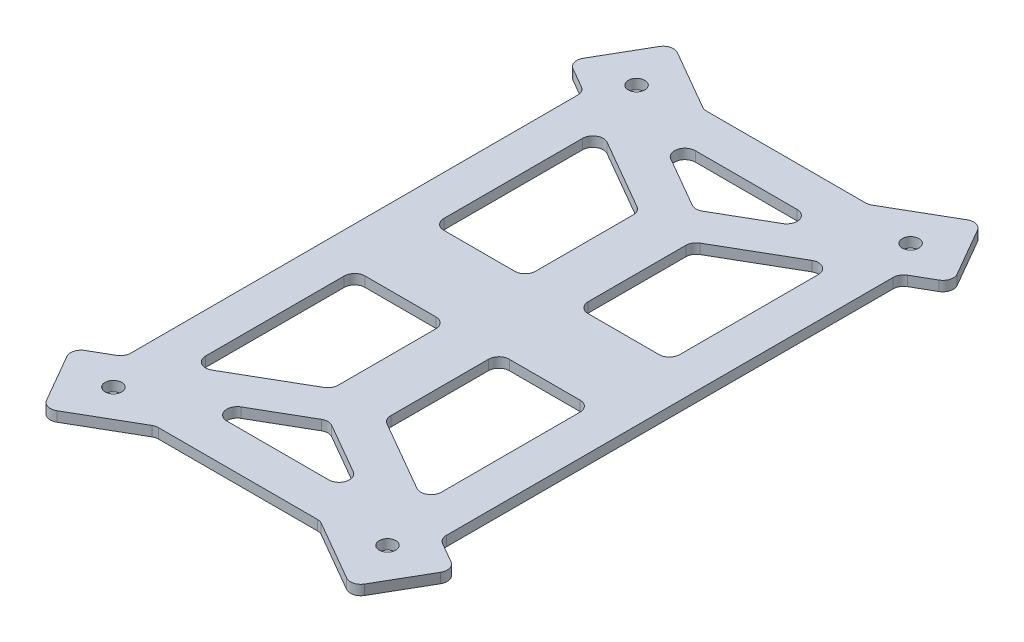
SolidWorks part; units mm, degrees
material "PA Type 6"
ref_plane "Front Plane" through (0, 0, 0) normal (0, 0, 1) x (1, 0, 0)
ref_plane "Top Plane" through (0, 0, 0) normal (0, 1, 0) x (1, 0, 0)
ref_plane "Right Plane" through (0, 0, 0) normal (1, 0, 0) x (0, 0, -1)
sketch "UPR FRAME PLATE ORIG SKETCH" plane through (0, 0, 0) normal (0, 1, 0) x (1, 0, 0)
  line L0 (-16.51, -144.7038) -> (-11.43, -142.1638)
  line L1 (-20.2311, 0) -> (20.2311, 0)
  line L2 (-24.0411, -3.81) -> (-24.0411, -144.7038)
  line L3 (-24.0411, -144.7038) -> (24.0411, -144.7038)
  line L4 (24.0411, -3.81) -> (24.0411, -144.7038)
  line L5 (-11.43, -142.1638) -> (11.43, -142.1638)
  line L6 (11.43, -142.1638) -> (16.51, -144.7038)
  line L7 (0, -144.7038) -> (0, 0) construction
  line L8 (-20.955, -60.6425) -> (20.955, -60.6425) construction
  line L9 (-18.034, -5.08) -> (18.034, -5.08) construction
  line L10 (-20.955, -140.6398) -> (20.955, -140.6398) construction
  circle A0 centre (20.955, -60.6425) radius 4.064
  circle A1 centre (-20.955, -60.6425) radius 4.064
  circle A2 centre (-20.955, -60.6425) radius 1.27
  circle A3 centre (20.955, -60.6425) radius 1.27
  circle A4 centre (-18.034, -5.08) radius 1.27
  circle A5 centre (18.034, -5.08) radius 1.27
  circle A6 centre (-20.955, -140.6398) radius 4.064
  circle A7 centre (20.955, -140.6398) radius 4.064
  circle A8 centre (-20.955, -140.6398) radius 1.27
  circle A9 centre (20.955, -140.6398) radius 1.27
  arc A10 (24.0411, -3.81) -> (20.2311, 0) centre (20.2311, -3.81) ccw
  arc A11 (-20.2311, 0) -> (-24.0411, -3.81) centre (-20.2311, -3.81) ccw
  point P4 (0, 0)
  point P15 (0, -60.6425)
  point P23 (0, -5.08)
  point P28 (0, -140.6398)
  point P35 (-24.0411, 0)
  dimension "D6" = 50.038
  dimension "D7" = 41.91
  dimension "D10" = 2.54
  dimension "D12" = 3.81
  dimension "D13" = 8.128
  dimension "D1" = 144.7038
  dimension "D2" = 48.0822
  dimension "D3" = 2.54
  dimension "D4" = 22.86
  dimension "D5" = 33.02
  dimension "D8" = 36.068
  dimension "D9" = 5.08
  dimension "D11" = 60.6425
sketch "Sketch2" plane through (0, 0, 0) normal (0, 1, 0) x (1, 0, 0)
  line L0 (0, -144.7038) -> (0, 0) construction
  line L1 (-24.13, -58.7311) -> (24.13, -58.7311)
  line L2 (-24.13, -58.7311) -> (-24.13, -142.5511)
  line L3 (-24.13, -142.5511) -> (24.13, -142.5511)
  line L4 (24.13, -58.7311) -> (24.13, -142.5511)
  line L5 (-20.955, -60.6425) -> (-20.955, -140.6398) construction
  line L6 (-20.955, -100.6411) -> (-46.355, -100.6411) construction
  circle A0 centre (-20.955, -60.6425) radius 1.27 construction
  circle A1 centre (20.955, -60.6425) radius 1.27 construction
  circle A2 centre (-20.955, -140.6398) radius 1.27 construction
  circle A3 centre (20.955, -140.6398) radius 1.27 construction
  circle A4 centre (-20.955, -60.6425) radius 1.27
  circle A5 centre (20.955, -60.6425) radius 1.27
  circle A6 centre (-20.955, -140.6398) radius 1.27
  circle A7 centre (20.955, -140.6398) radius 1.27
  point P16 (0, -58.7311)
  point P21 (-24.13, -100.6411)
  dimension "D1" = 83.82
  dimension "D2" = 48.26
extrude "Boss-Extrude1" add sketch "Sketch2" along normal blind 1.524 contours L4 L1 L2 L3 A7 A6 A5 A4
sketch "Sketch3" plane through (0, 0, 0) normal (0, 1, 0) x (1, 0, 0)
  line L0 (20.955, -60.6425) -> (26.4543, -57.4675) construction
  line L1 (-2.921, -67.6816) -> (23.5333, -52.4082)
  line L2 (-2.921, -67.6816) -> (2.921, -77.8002)
  line L3 (23.5333, -52.4082) -> (29.3753, -62.5268)
  line L4 (2.921, -77.8002) -> (29.3753, -62.5268)
  line L5 (-2.921, -67.6816) -> (29.3753, -62.5268) construction
  line L6 (23.5333, -52.4082) -> (2.921, -77.8002) construction
  line L8 (-24.13, -58.7311) -> (24.13, -58.7311) construction
  line L9 (0, -58.7312) -> (0, 0) construction
  circle A0 centre (20.955, -60.6425) radius 1.27 construction
  circle A1 centre (20.955, -60.6425) radius 1.27
  point P3 (26.4543, -57.4675)
  point P4 (13.2271, -65.1042)
  point P14 (0, -72.7409)
  dimension "D1" = 11.684
  dimension "D2" = 30
  dimension "D3" = 6.35
extrude "Boss-Extrude2" add sketch "Sketch3" along normal through all
ref_plane "CNTR OF LENGTH PLANE" through (0, 0, 100.6411) normal (0, 0, 1) x (1, 0, 0)
mirror "Mirror1" about plane through (0, 0, 100.6411) normal (0, 0, 1) of "Boss-Extrude2"
mirror "Mirror2" about plane through (0, 0, 0) normal (1, 0, 0) of "Mirror1", "Boss-Extrude2"
sketch "Sketch4" plane through (0, 1.524, 0) normal (0, 1, 0) x (1, 0, 0)
  line L0 (-0.8382, -100.6411) -> (0.8382, -100.6411) construction
  line L1 (-18.034, -94.6086) -> (18.034, -94.6086)
  line L2 (-18.034, -94.6086) -> (-18.034, -106.6736)
  line L3 (-18.034, -106.6736) -> (18.034, -106.6736)
  line L4 (18.034, -94.6086) -> (18.034, -106.6736)
  line L5 (0, -58.7312) -> (0, 0) construction
  line L6 (24.13, -65.5552) -> (24.13, -135.7271) construction
  line L8 (-4.0259, -64.8272) -> (4.0259, -64.8272)
  line L9 (-4.0259, -64.8272) -> (-4.0259, -136.4551)
  line L10 (-4.0259, -136.4551) -> (4.0259, -136.4551)
  line L11 (4.0259, -64.8272) -> (4.0259, -136.4551)
  line L12 (13.707, -64.8272) -> (0, -72.7409)
  line L13 (2.921, -77.8002) -> (29.3753, -62.5268) construction
  line L14 (0, -72.7409) -> (0, -64.8272)
  line L15 (4.0259, -64.8272) -> (13.707, -64.8272)
  line L16 (-12.5816, -58.7311) -> (12.5816, -58.7311) construction
  line L17 (4.0259, -77.1623) -> (18.034, -69.0747)
  line L18 (18.034, -69.0747) -> (18.034, -94.6086)
  point P4 (18.034, -100.6411)
  point P7 (0, -94.6086)
  point P16 (0, -64.8272)
  point P17 (4.0259, -100.6411)
  dimension "D1" = 12.065
  dimension "D2" = 6.096
  dimension "D3" = 8.0518
  dimension "D4" = 6.096
extrude "Cut-Extrude1" cut sketch "Sketch4" against normal blind 1.524 contours L18 L17 L11 L1 | L15 L11 L12 | L14 L12 L11 L8
mirror "Mirror3" about plane through (0, 0, 0) normal (1, 0, 0) of "Cut-Extrude1"
mirror "Mirror4" about plane through (0, 0, 100.6411) normal (0, 0, 1) of "Mirror3", "Cut-Extrude1"
fillet "Fillet1" radius 1.5875 38 edges at (-13.707, 0.762, 136.4551) (0, 0.762, 128.5414) (13.707, 0.762, 136.4551) (13.707, 0.762, 64.8272) (0, 0.762, 72.7409) (-13.707, 0.762, 64.8272) (-29.3753, 0.762, 138.7555) (-23.5333, 0.762, 148.8741) (-12.5816, 0.762, 142.5512) (12.5816, 0.762, 142.5512) (23.5333, 0.762, 148.8741) (29.3753, 0.762, 138.7555) (24.13, 0.762, 135.7271) (24.13, 0.762, 65.5552) (29.3753, 0.762, 62.5268) (23.5333, 0.762, 52.4082) (12.5816, 0.762, 58.7311) (-12.5816, 0.762, 58.7311) (-23.5333, 0.762, 52.4082) (-29.3753, 0.762, 62.5268) (-24.13, 0.762, 65.5552) (-24.13, 0.762, 135.7271) (18.034, 0.762, 94.6086) (4.0259, 0.762, 94.6086) (4.0259, 0.762, 77.1623) (18.034, 0.762, 69.0747) (-4.0259, 0.762, 94.6086) (-18.034, 0.762, 94.6086) (-18.034, 0.762, 69.0747) (-18.034, 0.762, 106.6736) (-4.0259, 0.762, 106.6736) (-4.0259, 0.762, 124.12) (-18.034, 0.762, 132.2076) (4.0259, 0.762, 124.12) (4.0259, 0.762, 106.6736) (18.034, 0.762, 106.6736) (18.034, 0.762, 132.2076) (-4.0259, 0.762, 77.1623)
